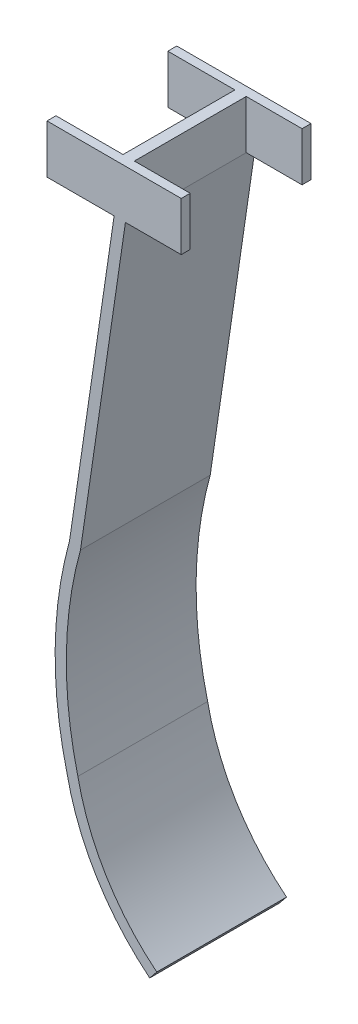
SolidWorks part; units mm, degrees
ref_plane "前视基准面" through (0, 0, 0) normal (0, 0, 1) x (1, 0, 0)
ref_plane "上视基准面" through (0, 0, 0) normal (0, 1, 0) x (1, 0, 0)
ref_plane "右视基准面" through (0, 0, 0) normal (1, 0, 0) x (0, 0, -1)
sketch "草图2" plane through (0, 0, 0) normal (0, 0, 1) x (1, 0, 0)
  line L25 (-37.8033, 45.7887) -> (-42.789, 11.8271)
  line L26 (-37.8033, 45.7887) -> (-45.3033, 45.7887)
  line L27 (-45.3033, 45.7887) -> (-45.3033, 51.2273)
  line L28 (-45.3033, 51.2273) -> (-30.3033, 51.2273)
  line L29 (-30.3033, 51.2273) -> (-30.3033, 46.2468)
  line L30 (-37.8033, 45.7887) -> (-30.3033, 45.7887)
  line L31 (-30.3033, 45.7887) -> (-30.3033, 46.2468)
  line L32 (-36.3563, 47.0387) -> (-41.5636, 11.5683) construction
  line L33 (-33.8248, -25.9691) -> (-33.0379, -24.998)
  line L34 (-36.5399, 45.7887) -> (-41.5636, 11.5683)
  line L35 (-36.3563, 47.0387) -> (-44.0533, 47.0387) construction
  line L36 (-44.0533, 47.0387) -> (-44.0533, 49.9773) construction
  line L37 (-44.0533, 49.9773) -> (-31.5533, 49.9773) construction
  line L38 (-31.5533, 49.9773) -> (-31.5533, 46.2468) construction
  arc A14 (-42.789, 11.8271) -> (-43.0716, -10.7527) centre (0, 0) ccw
  arc A15 (-43.0716, -10.7527) -> (-33.8248, -25.9691) centre (-17.1948, -5.4456) ccw
  arc A16 (-41.5636, 11.5683) -> (-41.8524, -10.4758) centre (0, 0) ccw
  arc A17 (-41.8524, -10.4758) -> (-33.0379, -24.998) centre (-17.1948, -5.4456) ccw
  dimension "D7" = 15
  dimension "D8" = 7.5
  dimension "D9" = 1.25
extrude "凸台-拉伸1" add sketch "草图2" along normal blind 14.5 contours L30 L31 L29 L28 L27 L26 | A17 A16 L34 L30 L25 A14 A15 L33
sketch "草图3" plane through (0, 45.7887, 0) normal (0, -1, 0) x (1, 0, 0)
  line L0 (-45.3033, 13.5) -> (-37.8033, 13.5)
  line L1 (-45.3033, 14.5) -> (-45.3033, 0) construction
  line L2 (-37.8033, 14.5) -> (-37.8033, 0) construction
  line L3 (-37.8033, 13.5) -> (-37.8033, 1)
  line L4 (-37.8033, 1) -> (-45.3033, 1)
  line L5 (-45.3033, 1) -> (-45.3033, 13.5)
  dimension "D1" = 1
  dimension "D2" = 1
extrude "切除-拉伸1" cut sketch "草图3" against normal blind 14.5
sketch "草图4" plane through (0, 45.7887, 0) normal (0, -1, 0) x (1, 0, 0)
  line L0 (-30.3033, 1) -> (-36.5399, 1)
  line L1 (-30.3033, 14.5) -> (-30.3033, 0) construction
  line L2 (-36.5399, 14.5) -> (-36.5399, 0) construction
  line L3 (-36.5399, 1) -> (-36.5399, 13.5)
  line L4 (-36.5399, 13.5) -> (-30.3033, 13.5)
  line L5 (-30.3033, 13.5) -> (-30.3033, 1)
  dimension "D1" = 1
  dimension "D2" = 1
extrude "切除-拉伸2" cut sketch "草图4" against normal blind 14.5
